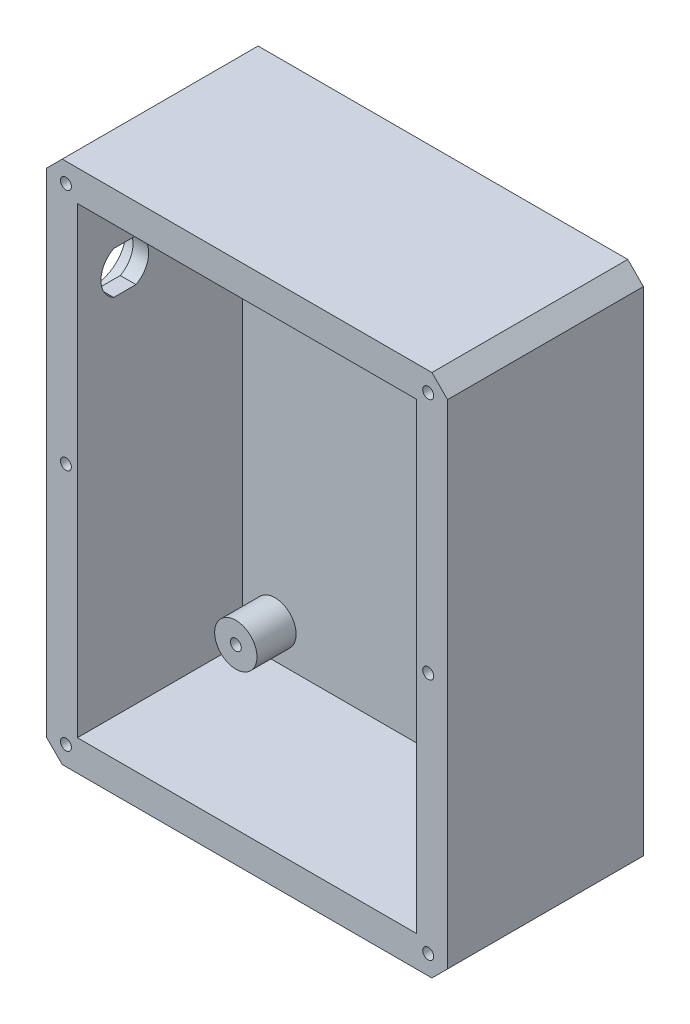
SolidWorks part; units mm, degrees
ref_plane "Front Plane" through (0, 0, 0) normal (0, 0, 1) x (1, 0, 0)
ref_plane "Top Plane" through (0, 0, 0) normal (0, 1, 0) x (1, 0, 0)
ref_plane "Right Plane" through (0, 0, 0) normal (1, 0, 0) x (0, 0, -1)
sketch "Sketch1" plane through (0, 0, 0) normal (0, 0, 1) x (1, 0, 0)
  line L0 (-27.5, 0) -> (27.5, 0) construction
  line L1 (-27.5, -37.5) -> (27.5, -37.5)
  line L2 (-27.5, -37.5) -> (-27.5, 37.5)
  line L3 (-27.5, 37.5) -> (27.5, 37.5)
  line L4 (27.5, -37.5) -> (27.5, 37.5)
  line L5 (-27.5, -37.5) -> (27.5, 37.5) construction
  line L6 (-27.5, 37.5) -> (27.5, -37.5) construction
  line L7 (0, -37.5) -> (0, 37.5) construction
  circle A0 centre (-22.225, 32.004) radius 0.889
  circle A1 centre (-22.225, -32.004) radius 0.889
  circle A2 centre (22.225, -32.004) radius 0.889
  circle A3 centre (22.225, 32.004) radius 0.889
  point P0 (0, 0)
  point P11 (0, 0)
  point P14 (0, 0)
  dimension "D3" = 64.008
  dimension "D5" = 1.778
  dimension "D1" = 55
  dimension "D2" = 75
  dimension "D4" = 44.45
extrude "Boss-Extrude1" add sketch "Sketch1" along normal blind 5
sketch "Sketch2" plane through (0, 0, 0) normal (0, 0, -1) x (-1, 0, 0)
  line L4 (-27.5, 37.5) -> (-27.5, -37.5)
  line L5 (-27.5, -37.5) -> (27.5, -37.5)
  line L6 (27.5, -37.5) -> (27.5, 37.5)
  line L7 (27.5, 37.5) -> (-27.5, 37.5)
  line L8 (-27.5, 37.5) -> (-27.5, -37.5)
  line L9 (-27.5, -37.5) -> (27.5, -37.5)
  line L10 (27.5, -37.5) -> (27.5, 37.5)
  line L11 (27.5, 37.5) -> (-27.5, 37.5)
  line L16 (-32.5, 42.5) -> (-32.5, -42.5)
  line L17 (-32.5, -42.5) -> (32.5, -42.5)
  line L18 (32.5, -42.5) -> (32.5, 42.5)
  line L19 (32.5, 42.5) -> (-32.5, 42.5)
  line L20 (-32.5, 42.5) -> (-32.5, -42.5)
  line L21 (-32.5, -42.5) -> (32.5, -42.5)
  line L22 (32.5, -42.5) -> (32.5, 42.5)
  line L23 (32.5, 42.5) -> (-32.5, 42.5)
  dimension "D1" = 0
  dimension "D2" = 5
extrude "Boss-Extrude2" add sketch "Sketch2" against normal blind 31.75
sketch "Sketch3" plane through (-32.5, 0, 0) normal (-1, 0, 0) x (0, 0, 1)
  line L0 (20.193, 24.8) -> (27.94, 24.8) construction
  line L1 (25.8682, 21.371) -> (22.2648, 21.371)
  line L2 (25.8682, 28.229) -> (22.2648, 28.229)
  line L3 (31.75, -42.5) -> (31.75, 42.5) construction
  line L4 (31.75, 37.5) -> (5, 37.5) construction
  arc A0 (22.2648, 28.229) -> (22.2648, 21.371) centre (24.0665, 24.8) ccw
  arc A1 (25.8682, 21.371) -> (25.8682, 28.229) centre (24.0665, 24.8) ccw
  circle A2 centre (24.0665, 24.8) radius 5.1435 construction
  point P4 (24.0665, 24.8)
  point P9 (29.21, 24.8)
  dimension "D1" = 7.747
  dimension "D3" = 10.287
  dimension "D2" = 6.858
  dimension "D4" = 2.54
  dimension "D5" = 12.7
extrude "Cut-Extrude1" cut sketch "Sketch3" against normal up to next
sketch "Sketch4" plane through (-32.5, 0, 0) normal (-1, 0, 0) x (0, 0, 1)
  arc A0 (22.2648, 28.229) -> (22.2648, 21.371) centre (24.0665, 24.8) ccw construction
  arc A1 (22.2648, 28.229) -> (22.2648, 21.371) centre (24.0665, 24.8) ccw construction
  circle A2 centre (24.0665, 24.8) radius 5.207
  dimension "D1" = 10.414
extrude "Cut-Extrude2" cut sketch "Sketch4" against normal offset from surface (2.46 mm away) 2.54 up to face at (-27.5, 24.8, 24.0665)
chamfer "Chamfer1" distance 2.54 angle 45 4 edges at (-32.5, 42.5, 15.875) (32.5, 42.5, 15.875) (32.5, -42.5, 15.875) (-32.5, -42.5, 15.875)
sketch "Sketch5" plane through (0, 0, 31.75) normal (0, 0, 1) x (1, 0, 0)
  line L0 (27.5, 37.5) -> (31.23, 41.23) construction
  line L1 (32.5, 39.96) -> (29.96, 42.5) construction
  line L2 (0, 0) -> (50000, 0) construction
  line L3 (0, 0) -> (0, -50000) construction
  circle A0 centre (29.365, 39.365) radius 0.889
  circle A1 centre (29.365, -39.365) radius 0.889
  circle A2 centre (-29.365, -39.365) radius 0.889
  circle A3 centre (-29.365, 39.365) radius 0.889
  circle A4 centre (29.365, 0) radius 0.889
  circle A5 centre (-29.365, 0) radius 0.889
  point P20 (29.8242, 0)
  dimension "D1" = 1.778
extrude "Cut-Extrude3" cut sketch "Sketch5" against normal blind 19.05
sketch "Sketch6" plane through (0, 0, 5) normal (0, 0, 1) x (1, 0, 0)
  circle A0 centre (-22.225, 32.004) radius 0.889 construction
  circle A1 centre (-22.225, -32.004) radius 0.889 construction
  circle A2 centre (22.225, -32.004) radius 0.889 construction
  circle A3 centre (22.225, 32.004) radius 0.889 construction
  circle A4 centre (-22.225, 32.004) radius 0.889
  circle A5 centre (-22.225, -32.004) radius 0.889
  circle A6 centre (22.225, -32.004) radius 0.889
  circle A7 centre (22.225, 32.004) radius 0.889
  circle A8 centre (-22.225, 32.004) radius 3.429
  circle A9 centre (-22.225, -32.004) radius 3.429
  circle A10 centre (22.225, -32.004) radius 3.429
  circle A11 centre (22.225, 32.004) radius 3.429
  dimension "D1" = 2.54
extrude "Boss-Extrude3" add sketch "Sketch6" along normal blind 6.35
